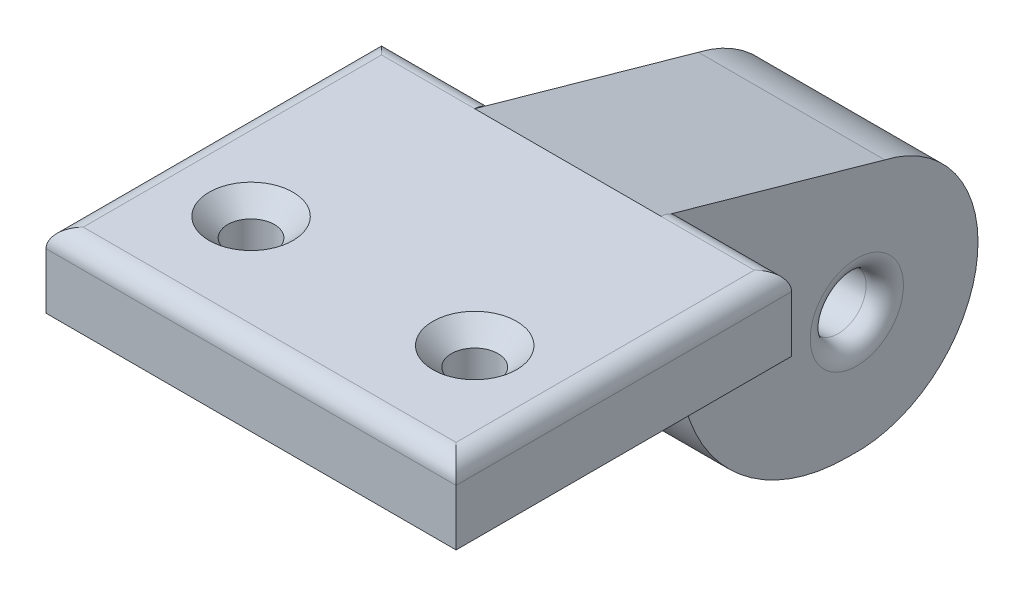
SolidWorks part; units mm, degrees
ref_plane "Front Plane" through (0, 0, 0) normal (0, 0, 1) x (1, 0, 0)
ref_plane "Top Plane" through (0, 0, 0) normal (0, 1, 0) x (1, 0, 0)
ref_plane "Right Plane" through (0, 0, 0) normal (1, 0, 0) x (0, 0, -1)
sketch "Sketch1" plane through (0, 0, 0) normal (0, 1, 0) x (1, 0, 0)
  line L1 (-8.2409, 25.3577) -> (2.7591, 25.3577)
  line L2 (-8.2409, 25.3577) -> (-8.2409, 7.3577)
  line L3 (-8.2409, 7.3577) -> (2.7591, 7.3577)
  line L4 (2.7591, 25.3577) -> (2.7591, 7.3577)
  line L5 (-8.2409, 25.3577) -> (-3.2409, 25.3577)
  line L6 (-8.2409, 25.3577) -> (-8.2409, 36.3577)
  line L7 (-8.2409, 36.3577) -> (-3.2409, 36.3577)
  line L8 (-3.2409, 25.3577) -> (-3.2409, 36.3577)
  dimension "D1" = 18
  dimension "D2" = 11
  dimension "D3" = 6
  dimension "D4" = 11
extrude "Boss-Extrude1" add sketch "Sketch1" along normal blind 4 contours L4 L1 L2 L3 | L1 L8 L7 L6
sketch "Sketch2" plane through (-3.2409, 0, 0) normal (1, 0, 0) x (0, 0, -1)
  line L0 (36.3577, 4) -> (36.3577, 0) construction
  line L1 (25.3577, 0) -> (34.5379, 0)
  line L2 (25.3577, 0) -> (25.3577, -12.1921)
  line L3 (25.3577, -12.1921) -> (34.5379, -12.1921)
  line L4 (34.5379, 0) -> (34.5379, -12.1921)
  circle A0 centre (34.8577, -5.7) radius 1.5
  arc A1 (34.5379, -12.1921) -> (36.3577, 0.6246) centre (34.8577, -5.7) ccw
  line M6 (25.3577, 0) -> (36.3577, 0)
  line M7 (36.3577, 0) -> (36.3577, 4)
  dimension "D2" = 9.5
  dimension "D1" = 5.7
extrude "Boss-Extrude2" add sketch "Sketch2" against normal blind 5 contours A0 L4 L2 L3 M6 | L4 A1 A0 M7 M6
mirror "Mirror1" about plane through (-8.2409, 4, 0) normal (1, 0, 0) of "Boss-Extrude2", "Boss-Extrude1"
sketch "Sketch3" plane through (0, 4, 0) normal (0, 1, 0) x (1, 0, 0)
  line L0 (-8.2409, 41.3577) -> (-8.2409, 7.0572) construction
  line L1 (-3.2409, 41.3577) -> (-13.2409, 41.3577) construction
  line L2 (2.7591, 25.3577) -> (2.7591, 7.3577) construction
  line L3 (-3.2409, 25.3577) -> (2.7591, 25.3577) construction
  circle A0 centre (-2.2409, 13.3577) radius 1.2484
  circle A2 centre (-14.2409, 13.3577) radius 1.2484
  dimension "D1" = 5
  dimension "D2" = 12
extrude "Cut-Extrude1" cut sketch "Sketch3" against normal blind 5
fillet "Fillet1" radius 1 7 edges at (-0.2409, 4, -25.3577) (-3.2409, -5.7, -36.3577) (-8.2409, 4, -7.3577) (-19.2409, 4, -16.3577) (-16.2409, 4, -25.3577) (2.7591, 4, -16.3577) (-13.2409, -5.7, -36.3577)
fillet "Fillet3" radius 2 1 edges at (-8.2409, 0, -25.3577)
fillet "Fillet4" radius 9 1 edges at (-8.2409, -12.1921, -25.3577)
sketch "Sketch4" plane through (-13.2409, 0, 0) normal (-1, 0, 0) x (0, 0, 1)
  line L0 (-36.3577, 0.6246) -> (-24.3577, 4)
  line L1 (-36.3577, 4) -> (-36.3577, 0.6246) construction
  line L2 (-36.3577, 0.6246) -> (-36.3577, 4)
  line L4 (-36.3577, 4) -> (-24.3577, 4)
extrude "Cut-Extrude2" cut sketch "Sketch4" against normal blind 10
chamfer "Chamfer1" distance 1 angle 45 2 edges at (-14.2409, 4, -14.6061) (-2.2409, 4, -12.1092)
equation "\"7cmmm\"=6.5"
